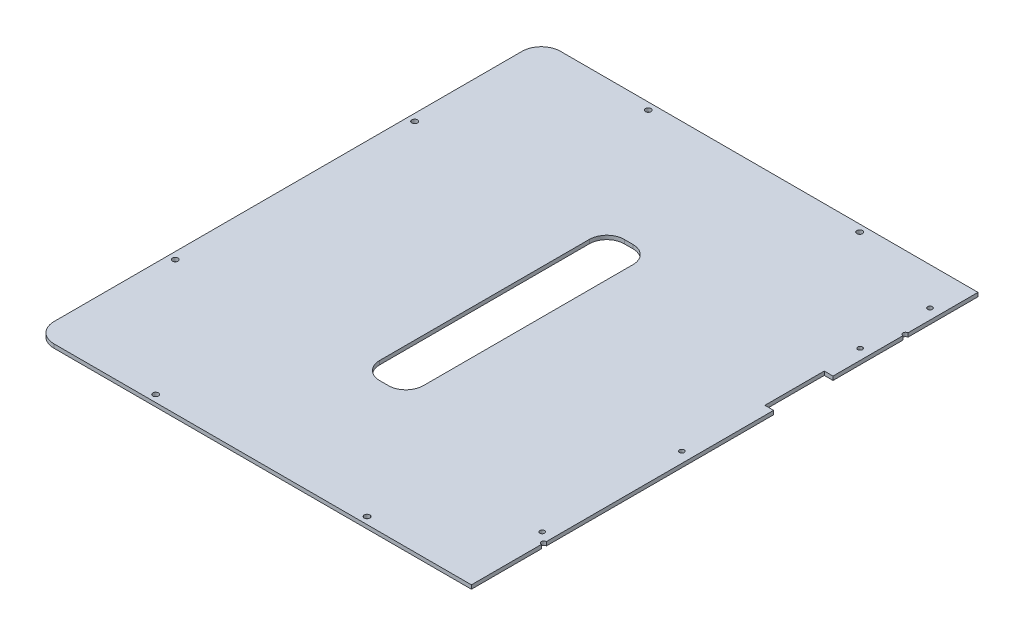
SolidWorks part; units mm, degrees
ref_plane "Front Plane" through (0, 0, 0) normal (0, 0, 1) x (1, 0, 0)
ref_plane "Top Plane" through (0, 0, 0) normal (0, 1, 0) x (1, 0, 0)
ref_plane "Right Plane" through (0, 0, 0) normal (1, 0, 0) x (0, 0, -1)
sketch "Sketch1" plane through (0, 0, 0) normal (0, 1, 0) x (1, 0, 0)
  line L0 (0, 145) -> (0, 141) construction
  line L1 (-239, 145) -> (239, 145)
  line L2 (-250, 134) -> (-250, -134)
  line L3 (-239, -145) -> (239, -145)
  line L4 (250, 134) -> (250, -134)
  line L5 (-250, 145) -> (250, -145) construction
  line L6 (-250, -145) -> (250, 145) construction
  line L7 (0, 0) -> (0, 79.598) construction
  line L8 (0, 0) -> (95.4216, 0) construction
  line L9 (-125, 30) -> (-125, -30) construction
  line L10 (-125, -30) -> (125, -30) construction
  line L11 (125, -30) -> (125, 30) construction
  line L12 (0, 62) -> (0, 28) construction
  line L13 (-127.5, -70) -> (-122.5, -70)
  line L14 (-137.5, -60) -> (-137.5, 60)
  line L15 (-127.5, 70) -> (-122.5, 70)
  line L16 (-112.5, -60) -> (-112.5, 60)
  line L17 (-137.5, -70) -> (-112.5, 70) construction
  line L18 (-137.5, 70) -> (-112.5, -70) construction
  line L19 (122.5, -70) -> (127.5, -70)
  line L20 (112.5, -60) -> (112.5, 60)
  line L21 (122.5, 70) -> (127.5, 70)
  line L22 (137.5, -60) -> (137.5, 60)
  line L23 (112.5, -70) -> (137.5, 70) construction
  line L24 (112.5, 70) -> (137.5, -70) construction
  line L25 (-5, 28) -> (5, 28)
  line L26 (-5, 28) -> (-5, 62)
  line L27 (-5, 62) -> (5, 62)
  line L28 (5, 28) -> (5, 62)
  line L29 (-5, 28) -> (5, 62) construction
  line L30 (-5, 62) -> (5, 28) construction
  arc A0 (-250, -134) -> (-239, -145) centre (-239, -134) ccw
  arc A1 (250, -134) -> (239, -145) centre (239, -134) cw
  arc A2 (250, 134) -> (239, 145) centre (239, 134) ccw
  arc A3 (-239, 145) -> (-250, 134) centre (-239, 134) ccw
  circle A4 centre (63.75, 141) radius 1.6
  circle A5 centre (184.75, 141) radius 1.6
  circle A6 centre (246, 68.5) radius 1.6
  circle A7 centre (0, 103.5) radius 1.4
  circle A8 centre (0, -103.5) radius 1.4
  arc A9 (137.5, 60) -> (127.5, 70) centre (127.5, 60) ccw
  arc A10 (122.5, 70) -> (112.5, 60) centre (122.5, 60) ccw
  arc A11 (137.5, -60) -> (127.5, -70) centre (127.5, -60) cw
  arc A12 (112.5, -60) -> (122.5, -70) centre (122.5, -60) ccw
  arc A13 (-112.5, -60) -> (-122.5, -70) centre (-122.5, -60) cw
  arc A14 (-127.5, -70) -> (-137.5, -60) centre (-127.5, -60) cw
  arc A15 (-112.5, 60) -> (-122.5, 70) centre (-122.5, 60) ccw
  arc A16 (-127.5, 70) -> (-137.5, 60) centre (-127.5, 60) ccw
  circle A17 centre (-246, 68.5) radius 1.6
  circle A18 centre (-184.75, 141) radius 1.6
  circle A19 centre (-63.75, 141) radius 1.6
  circle A20 centre (184.75, -141) radius 1.6
  circle A21 centre (246, -68.5) radius 1.6
  circle A22 centre (63.75, -141) radius 1.6
  circle A23 centre (-63.75, -141) radius 1.6
  circle A24 centre (-184.75, -141) radius 1.6
  circle A25 centre (-246, -68.5) radius 1.6
  point P0 (0, 0)
  point P34 (-125, 0)
  point P41 (125, 0)
  point P76 (0, 45)
  dimension "D3" = 11
  dimension "D8" = 10
  dimension "D1" = 290
  dimension "D2" = 500
  dimension "D4" = 140
  dimension "D5" = 140
  dimension "D6" = 25
  dimension "D7" = 25
  dimension "D9" = 10
  dimension "D10" = 34
extrude "Boss-Extrude1" add sketch "Sketch1" along normal blind 2.2
sketch "Sketch2" plane through (0, 2.2, 0) normal (0, 1, 0) x (1, 0, 0)
  line L0 (0, 62) -> (0, 145) construction
  line L1 (5, 62) -> (-5, 62) construction
  line L2 (239, 145) -> (-239, 145) construction
  line L3 (0, 28) -> (0, -145) construction
  line L4 (-5, 28) -> (5, 28) construction
  line L5 (-239, -145) -> (239, -145) construction
  line L7 (-6, -98.5) -> (6, -98.5) construction
  line L8 (-6, -98.5) -> (-6, -18.5) construction
  line L9 (-6, -18.5) -> (6, -18.5) construction
  line L10 (6, -98.5) -> (6, -18.5) construction
  line L11 (-6, -98.5) -> (6, -18.5) construction
  line L12 (-6, -18.5) -> (6, -98.5) construction
  line L13 (-6, 83.5) -> (6, 83.5) construction
  line L14 (-6, 83.5) -> (-6, 123.5) construction
  line L15 (-6, 123.5) -> (6, 123.5) construction
  line L16 (6, 83.5) -> (6, 123.5) construction
  line L17 (-6, 83.5) -> (6, 123.5) construction
  line L18 (-6, 123.5) -> (6, 83.5) construction
  circle A0 centre (-6, -18.5) radius 1.35
  circle A1 centre (6, -18.5) radius 1.35
  circle A2 centre (-6, -98.5) radius 1.35
  circle A3 centre (6, -98.5) radius 1.35
  circle A4 centre (-6, 123.5) radius 1.35
  circle A5 centre (6, 123.5) radius 1.35
  circle A6 centre (-6, 83.5) radius 1.35
  circle A7 centre (6, 83.5) radius 1.35
  point P12 (0, -58.5)
  point P21 (0, 103.5)
  dimension "D1" = 12
  dimension "D2" = 40
extrude "Cut-Extrude1" cut sketch "Sketch2" against normal blind 59.2
sketch "Sketch4" plane through (0, 2.2, 0) normal (0, 1, 0) x (1, 0, 0)
  line L0 (239, 145) -> (-239, 145) construction
  line L1 (0, 145) -> (288.5775, 145)
  line L2 (0, 145) -> (0, -170.1469)
  line L3 (0, -170.1469) -> (288.5775, -170.1469)
  line L4 (288.5775, 145) -> (288.5775, -170.1469)
extrude "Cut-Extrude2" cut sketch "Sketch4" against normal up to surface (2.2 mm away) up to face at (-6, 0, -122.15)
